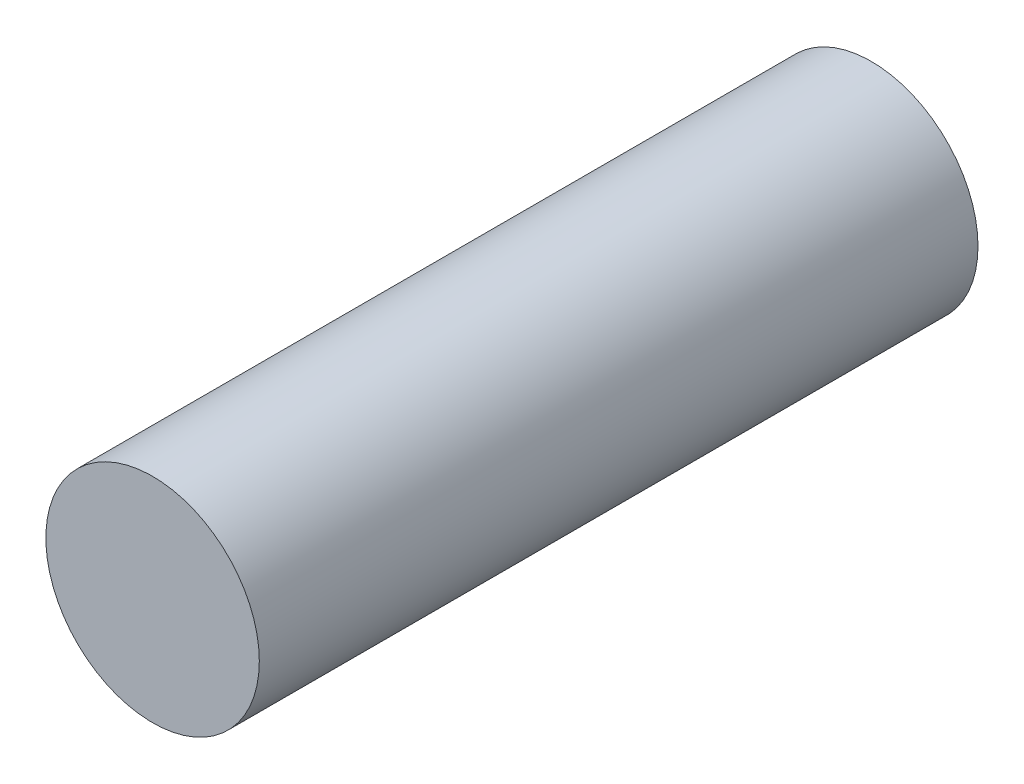
SolidWorks part; units mm, degrees
ref_plane "Front Plane" through (0, 0, 0) normal (0, 0, 1) x (1, 0, 0)
ref_plane "Top Plane" through (0, 0, 0) normal (0, 1, 0) x (1, 0, 0)
ref_plane "Right Plane" through (0, 0, 0) normal (1, 0, 0) x (0, 0, -1)
sketch "Sketch1" plane through (0, 0, 0) normal (0, 0, 1) x (1, 0, 0)
  circle A0 centre (0, 0) radius 7.62
  dimension "D1" = 15.24
extrude "Boss-Extrude1" add sketch "Sketch1" along normal blind 51.308
